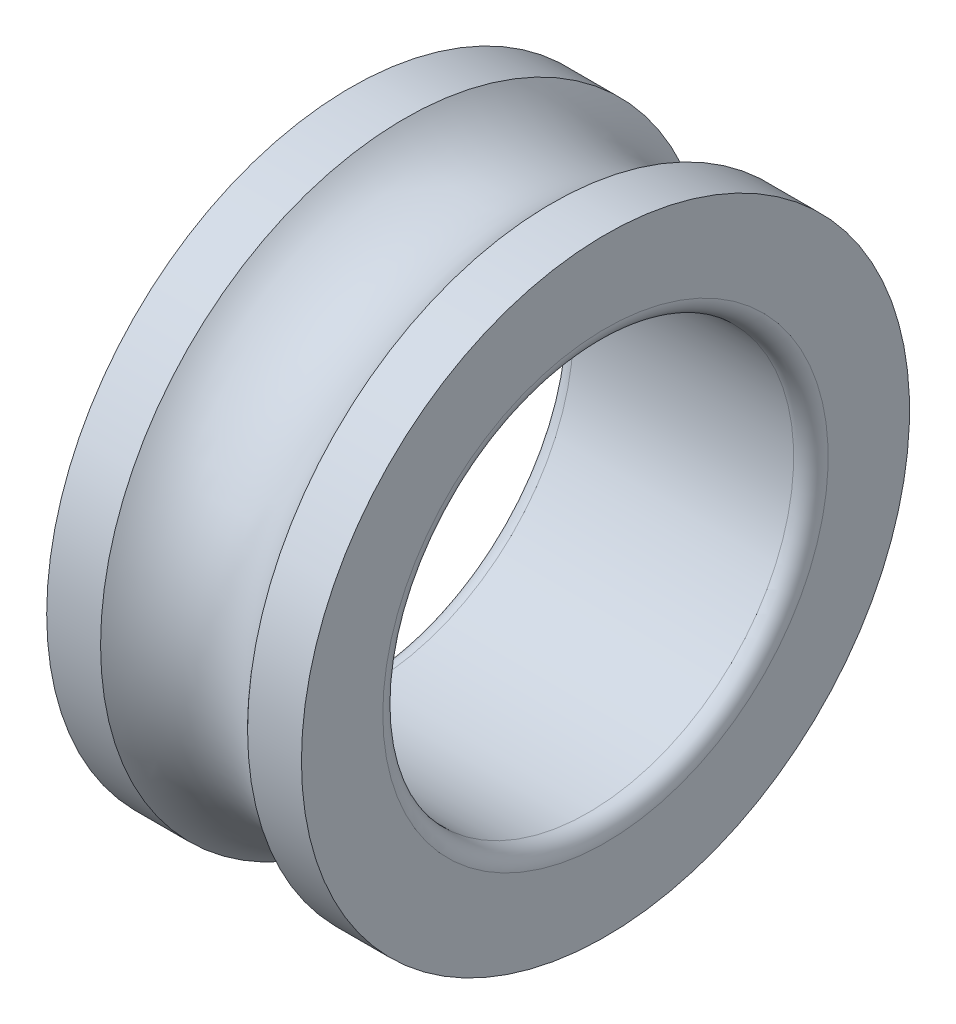
SolidWorks part; units mm, degrees
ref_plane "Front Plane" through (0, 0, 0) normal (0, 0, 1) x (1, 0, 0)
ref_plane "Top Plane" through (0, 0, 0) normal (0, 1, 0) x (1, 0, 0)
ref_plane "Right Plane" through (0, 0, 0) normal (1, 0, 0) x (0, 0, -1)
sketch "Sketch1" plane through (0, 0, 0) normal (0, 0, 1) x (1, 0, 0)
  line L0 (-1.7506, 0) -> (6.4249, 0) construction
  line L1 (-13.95, 25) -> (-13.95, 0) construction
  line L2 (-0.55, 25) -> (-27.35, 25)
  line L3 (1.55, 27.1) -> (1.55, 37)
  line L4 (1.55, 37) -> (-5.0057, 37)
  line L5 (-29.45, 27.1) -> (-29.45, 37)
  line L6 (1.55, 25) -> (-29.45, 37) construction
  line L7 (1.55, 37) -> (-29.45, 25) construction
  line L8 (-22.8943, 37) -> (-29.45, 37)
  arc A0 (-22.8943, 37) -> (-5.0057, 37) centre (-13.95, 45) ccw
  arc A1 (-0.55, 25) -> (1.55, 27.1) centre (-0.55, 27.1) ccw
  arc A2 (-27.35, 25) -> (-29.45, 27.1) centre (-27.35, 27.1) cw
  point P3 (-13.95, 31)
  dimension "D4" = 12
  dimension "D6" = 2.1
  dimension "D1" = 31
  dimension "D2" = 25
  dimension "D3" = 37
  dimension "D5" = 8
revolve "Revolve1" add sketch "Sketch1" angle 360 about L0
